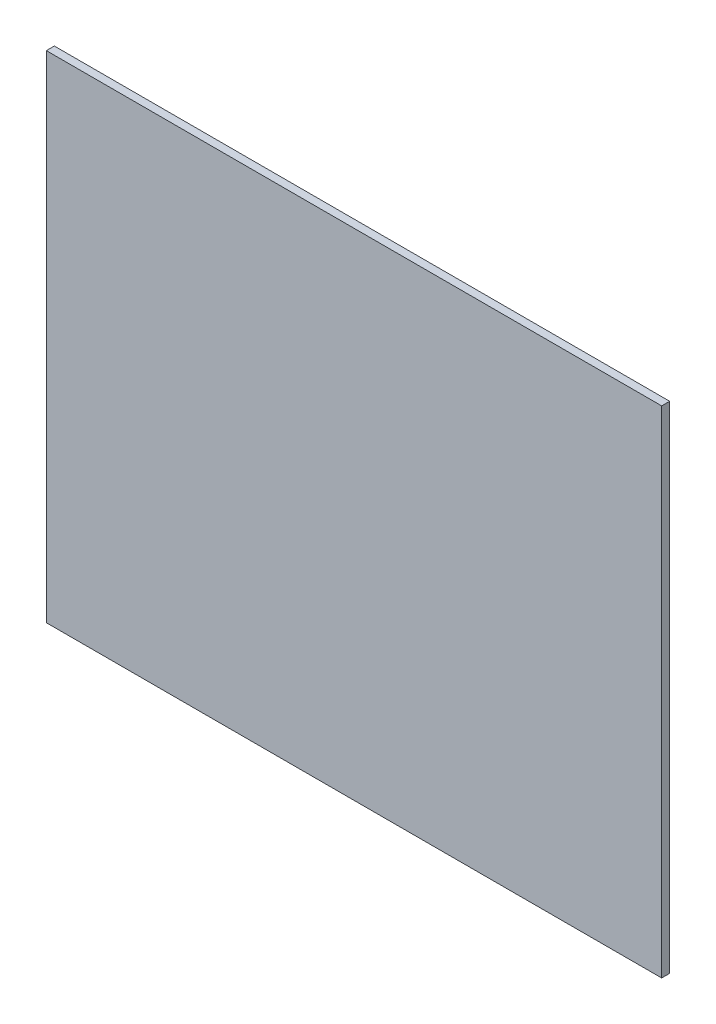
SolidWorks part; units mm, degrees
material "Custom Plastic"
ref_plane "Front Plane" through (0, 0, 0) normal (0, 0, 1) x (1, 0, 0)
ref_plane "Top Plane" through (0, 0, 0) normal (0, 1, 0) x (1, 0, 0)
ref_plane "Right Plane" through (0, 0, 0) normal (1, 0, 0) x (0, 0, -1)
sketch "Sketch1" plane through (0, 0, 0) normal (0, 0, 1) x (1, 0, 0)
  line L1 (0, 0) -> (154, 0)
  line L2 (0, 0) -> (0, -124)
  line L3 (0, -124) -> (154, -124)
  line L4 (154, 0) -> (154, -124)
  dimension "D1" = 154
  dimension "D2" = 124
extrude "Boss-Extrude1" add sketch "Sketch1" along normal blind 2
